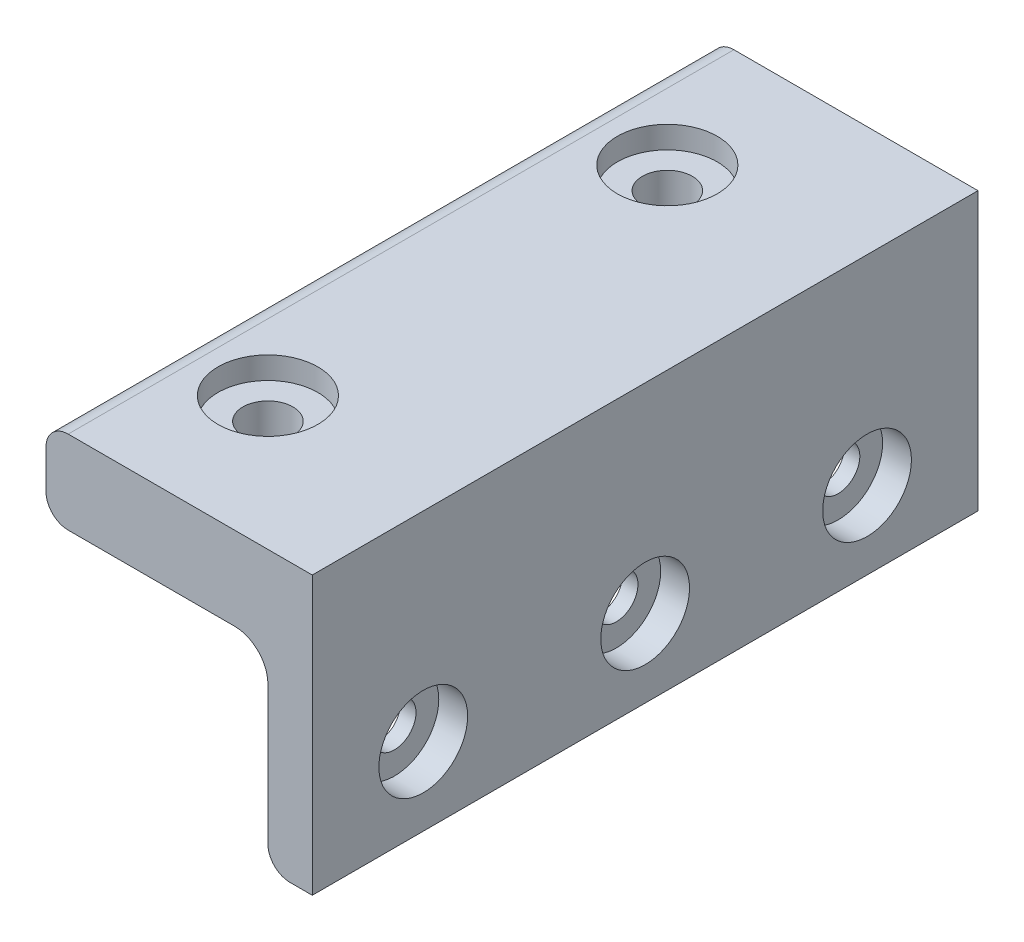
SolidWorks part; units mm, degrees
ref_plane "Front Plane" through (0, 0, 0) normal (0, 0, 1) x (1, 0, 0)
ref_plane "Top Plane" through (0, 0, 0) normal (0, 1, 0) x (1, 0, 0)
ref_plane "Right Plane" through (0, 0, 0) normal (1, 0, 0) x (0, 0, -1)
other "Configuration Table"
sketch "Sketch1" plane through (0, 0, 0) normal (0, 0, 1) x (1, 0, 0)
  line L0 (-22, 0) -> (0, 0)
  line L1 (0, 0) -> (0, -25)
  line L2 (0, -25) -> (-2, -25)
  line L3 (-4, -23) -> (-4, -10.5)
  line L4 (-7, -7.5) -> (-22, -7.5)
  line L5 (-24, -5.5) -> (-24, -2)
  arc A0 (-22, 0) -> (-24, -2) centre (-22, -2) ccw
  arc A1 (-22, -7.5) -> (-24, -5.5) centre (-22, -5.5) cw
  arc A2 (-2, -25) -> (-4, -23) centre (-2, -23) cw
  arc A3 (-4, -10.5) -> (-7, -7.5) centre (-7, -10.5) ccw
  point P9 (-24, 0)
  point P12 (-24, -7.5)
  point P15 (-4, -25)
  dimension "D5" = 2
  dimension "D6" = 3
  dimension "D1" = 25
  dimension "D2" = 24
  dimension "D3" = 7.5
  dimension "D4" = 4
extrude "Extrude1" add sketch "Sketch1" against normal blind 60
hole_wizard "CBORE for M3.5 Pan Head Machine Screw1" positions "Sketch4" profile "Sketch3" counterbore size "M3.5" standard "Ansi Metric" end condition through all
sketch "Sketch4" plane through (0, 0, 0) normal (1, 0, 0) x (0, 0, -1)
  line L0 (0, -25) -> (0, 0) construction
  line L1 (60, 0) -> (0, 0) construction
  point P0 (50, -18)
  point P1 (30, -18)
  point P3 (10, -18)
  dimension "D1" = 50
  dimension "D2" = 30
  dimension "D3" = 10
  dimension "D4" = 18
  dimension "D5" = 18
  dimension "D6" = 18
sketch "Sketch3" plane through (0, -18, -50) normal (0, 1, 0) x (0, 0, -1)
  line L0 (0, 0) -> (0, 24)
  line L1 (0, 24) -> (1.95, 24)
  line L3 (1.95, 24) -> (1.95, 2.6)
  line L4 (1.95, 2.6) -> (4, 2.6)
  line L5 (4, 2.6) -> (4, 0)
  line L7 (4, 0) -> (0, 0)
  line L11 (0, -6.35) -> (0, 107.95) construction
  dimension "Thru Hole Dia." = 3.9
  dimension "Thru Hole Depth" = 24
  dimension "C'Bore Dia." = 8
  dimension "C'Bore Depth" = 2.6
hole_wizard "CBORE for M4 Pan Head Machine Screw1" positions "Sketch6" profile "Sketch5" counterbore size "M4" standard "Ansi Metric" end condition through all
sketch "Sketch6" plane through (0, 0, 0) normal (0, 1, 0) x (-1, 0, 0)
  line L0 (0, 0) -> (22, 0) construction
  line L1 (0, -60) -> (0, 0) construction
  point P0 (16, -48)
  point P9 (16, -12)
  dimension "D1" = 48
  dimension "D2" = 16
  dimension "D3" = 16
  dimension "D4" = 12
sketch "Sketch5" plane through (-16, 0, -48) normal (1, 0, 0) x (0, 0, 1)
  line L0 (0, 0) -> (0, 25)
  line L1 (0, 25) -> (2.25, 25)
  line L3 (2.25, 25) -> (2.25, 2)
  line L4 (2.25, 2) -> (4.5, 2)
  line L5 (4.5, 2) -> (4.5, 0)
  line L7 (4.5, 0) -> (0, 0)
  line L11 (0, -6.35) -> (0, 107.95) construction
  dimension "Thru Hole Dia." = 4.5
  dimension "Thru Hole Depth" = 25
  dimension "C'Bore Dia." = 9
  dimension "C'Bore Depth" = 2
